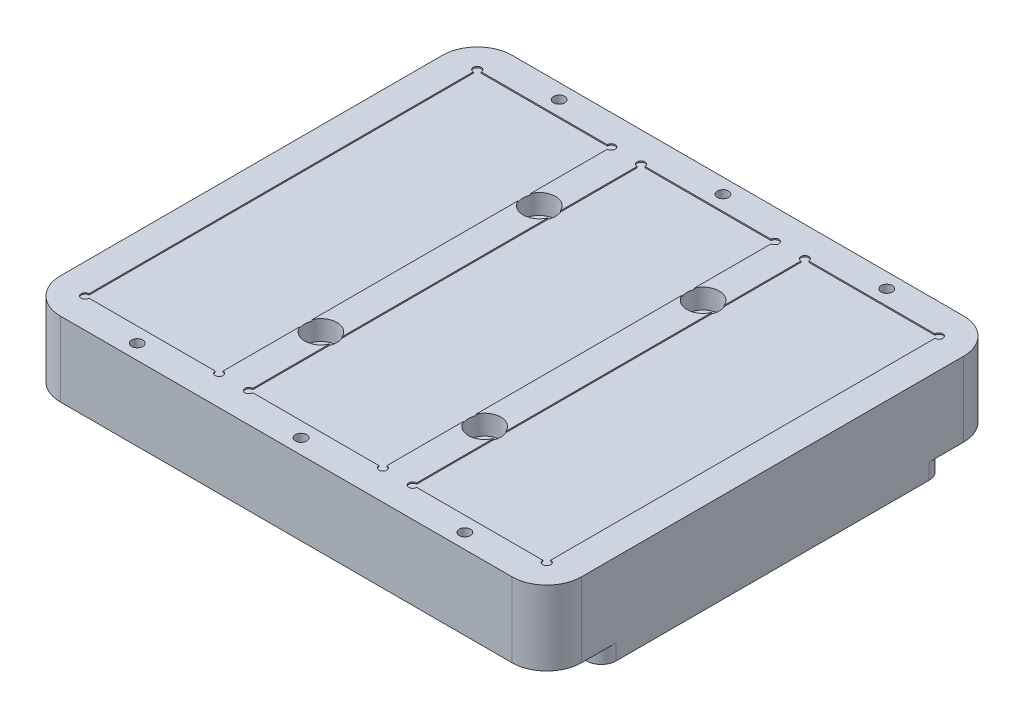
SolidWorks part; units mm, degrees
material "6061 Alloy"
ref_plane "Front Plane" through (0, 0, 0) normal (0, 0, 1) x (1, 0, 0)
ref_plane "Top Plane" through (0, 0, 0) normal (0, 1, 0) x (1, 0, 0)
ref_plane "Right Plane" through (0, 0, 0) normal (1, 0, 0) x (0, 0, -1)
sketch "Sketch1" plane through (0, 0, 0) normal (0, 1, 0) x (1, 0, 0)
  line L1 (-52.5, 34.5) -> (52.5, 34.5)
  line L2 (-52.5, 34.5) -> (-52.5, -34.5)
  line L3 (-52.5, -34.5) -> (52.5, -34.5)
  line L4 (52.5, 34.5) -> (52.5, -34.5)
  line L5 (-52.5, 34.5) -> (52.5, -34.5) construction
  line L6 (-52.5, -34.5) -> (52.5, 34.5) construction
  point P0 (0, 0)
  dimension "D1" = 105
  dimension "D2" = 69
extrude "Boss-Extrude1" add sketch "Sketch1" along normal blind 3.18
fillet "Fillet1" radius 3 4 edges at (-52.5, 1.59, -34.5) (52.5, 1.59, -34.5) (52.5, 1.59, 34.5) (-52.5, 1.59, 34.5)
sketch "Sketch2" plane through (0, 3.18, 0) normal (0, 1, 0) x (1, 0, 0)
  line L1 (-52.5, 45.5) -> (52.5, 45.5)
  line L2 (-52.5, 45.5) -> (-52.5, -45.5)
  line L3 (-52.5, -45.5) -> (52.5, -45.5)
  line L4 (52.5, 45.5) -> (52.5, -45.5)
  line L5 (-52.5, 45.5) -> (52.5, -45.5) construction
  line L6 (-52.5, -45.5) -> (52.5, 45.5) construction
  point P0 (0, 0)
  dimension "D1" = 105
  dimension "D2" = 91
extrude "Boss-Extrude2" add sketch "Sketch2" along normal blind 15
fillet "Fillet2" radius 7 4 edges at (52.5, 10.68, 45.5) (52.5, 10.68, -45.5) (-52.5, 10.68, -45.5) (-52.5, 10.68, 45.5)
sketch "Sketch3" plane through (0, 18.18, 0) normal (0, 1, 0) x (1, 0, 0)
  line L0 (-9.999, 0) -> (9.999, 0) construction
  line L1 (-46.5, 39.5) -> (-19.5, 39.5)
  line L2 (-46.5, 39.5) -> (-46.5, -39.5)
  line L3 (-46.5, -39.5) -> (-19.5, -39.5)
  line L4 (-19.5, 39.5) -> (-19.5, -39.5)
  line L5 (-46.5, 39.5) -> (-19.5, -39.5) construction
  line L6 (-46.5, -39.5) -> (-19.5, 39.5) construction
  line L7 (-52.5, 38.5) -> (-52.5, -38.5) construction
  point P0 (-33, 0)
  dimension "D1" = 27
  dimension "D2" = 79
  dimension "D3" = 6
extrude "Cut-Extrude1" cut sketch "Sketch3" against normal blind 0.25
ref_plane "Plane1" through (-33, 0, 0) normal (1, 0, 0) x (0, 0, -1)
hole_wizard "#4-40 Tapped Hole1" positions "Sketch7" profile "Sketch8" tap size "#4-40" standard "ANSI Inch"
sketch "Sketch7" plane through (0, 18.18, 0) normal (0, 1, 0) x (1, 0, 0)
  line L0 (-33, -9.999) -> (-33, 9.999) construction
  line L1 (-19.5, 39.5) -> (-46.5, 39.5) construction
  point P0 (-33, 42.5)
  dimension "D1" = 3
sketch "Sketch8" plane through (-33, 18.18, -42.5) normal (1, 0, 0) x (0, 0, 1)
  line L0 (0, 0) -> (0, 7.6792)
  line L1 (0, 7.6792) -> (1.1303, 7)
  line L2 (1.1303, 7) -> (1.1303, 0)
  line L5 (1.1303, 0) -> (0, 0)
  line L10 (0, 7.6792) -> (-1.1303, 7) construction
  line L11 (0, -6.35) -> (0, 107.95) construction
  dimension "Tap Drill Dia." = 2.2606
  dimension "Tap Drill Depth" = 7
  dimension "Drill Angle" = 118
cosmetic thread "Hole Thread1" parameters "D1"=5.69, "D2"=2.8448
mirror "Mirror5" about plane through (0, 0, 0) normal (0, 0, 1) of "#4-40 Tapped Hole1"
sketch "Sketch4" plane through (0, 18.18, 0) normal (0, 1, 0) x (1, 0, 0)
  circle A0 centre (-46.5, 39.5) radius 0.7937
  dimension "D1" = 1.5875
extrude "Cut-Extrude2" cut sketch "Sketch4" against normal up to surface (0.25 mm away) up to face at (-33, 17.93, 0)
mirror "Mirror1" about plane through (-33, 0, 0) normal (1, 0, 0) of "Cut-Extrude2"
mirror "Mirror2" about plane through (0, 0, 0) normal (0, 0, 1) of "Mirror1", "Cut-Extrude2"
pattern_linear "LPattern1" count 3 spacing 33 along (1, 0, 0) of "Cut-Extrude1", "Cut-Extrude2", "Mirror1", "Mirror2", "#4-40 Tapped Hole1", "Mirror5"
hole_wizard "CBORE for M3 SHCS1" positions "Sketch5" profile "Sketch6" counterbore size "M3" standard "ANSI Metric" end condition through all
sketch "Sketch5" plane through (0, 18.18, 0) normal (0, 1, 0) x (1, 0, 0)
  line L0 (-9.999, 0) -> (9.999, 0) construction
  line L1 (0, -9.999) -> (0, 9.999) construction
  point P0 (16.5, -22)
  dimension "D1" = 22
  dimension "D2" = 16.5
sketch "Sketch6" plane through (16.5, 18.18, 22) normal (1, 0, 0) x (0, 0, 1)
  line L0 (0, 0) -> (0, 18.18)
  line L1 (0, 18.18) -> (1.7, 18.18)
  line L3 (1.7, 18.18) -> (1.7, 4)
  line L4 (1.7, 4) -> (3.25, 4)
  line L5 (3.25, 4) -> (3.25, 0)
  line L7 (3.25, 0) -> (0, 0)
  line L11 (0, -6.35) -> (0, 107.95) construction
  dimension "Thru Hole Dia." = 3.4
  dimension "Thru Hole Depth" = 18.18
  dimension "C'Bore Dia." = 6.5
  dimension "C'Bore Depth" = 4
mirror "Mirror3" about plane through (0, 0, 0) normal (1, 0, 0) of "CBORE for M3 SHCS1"
mirror "Mirror4" about plane through (0, 0, 0) normal (0, 0, 1) of "Mirror3", "CBORE for M3 SHCS1"
hole_wizard "#2-56 Tapped Hole1" positions "Sketch9" profile "Sketch10" tap size "#2-56" standard "ANSI Inch"
sketch "Sketch9" plane through (0, 0, -45.5) normal (0, 0, -1) x (-1, 0, 0)
  line L0 (33, 15.8837) -> (33, 5.1773) construction
  line L2 (33, 9.999) -> (33, -9.999) construction
  line L3 (-45.5, 18.18) -> (45.5, 18.18) construction
  point P0 (30, 12.18)
  point P9 (36, 12.18)
  dimension "D1" = 6
  dimension "D2" = 6
sketch "Sketch10" plane through (-30, 12.18, -45.5) normal (1, 0, 0) x (0, 1, 0)
  line L0 (0, 0) -> (0, 6.2642)
  line L1 (0, 6.2642) -> (0.889, 5.73)
  line L2 (0.889, 5.73) -> (0.889, 0)
  line L5 (0.889, 0) -> (0, 0)
  line L10 (0, 6.2642) -> (-0.889, 5.73) construction
  line L11 (0, -6.35) -> (0, 107.95) construction
  dimension "Tap Drill Dia." = 1.778
  dimension "Tap Drill Depth" = 5.73
  dimension "Drill Angle" = 118
cosmetic thread "Hole Thread2" parameters "D1"=4.37, "D2"=2.1844
cosmetic thread "Hole Thread3" parameters "D1"=4.37, "D2"=2.1844
pattern_linear "LPattern2" count 3 spacing 33 along (1, 0, 0) of "#2-56 Tapped Hole1"
